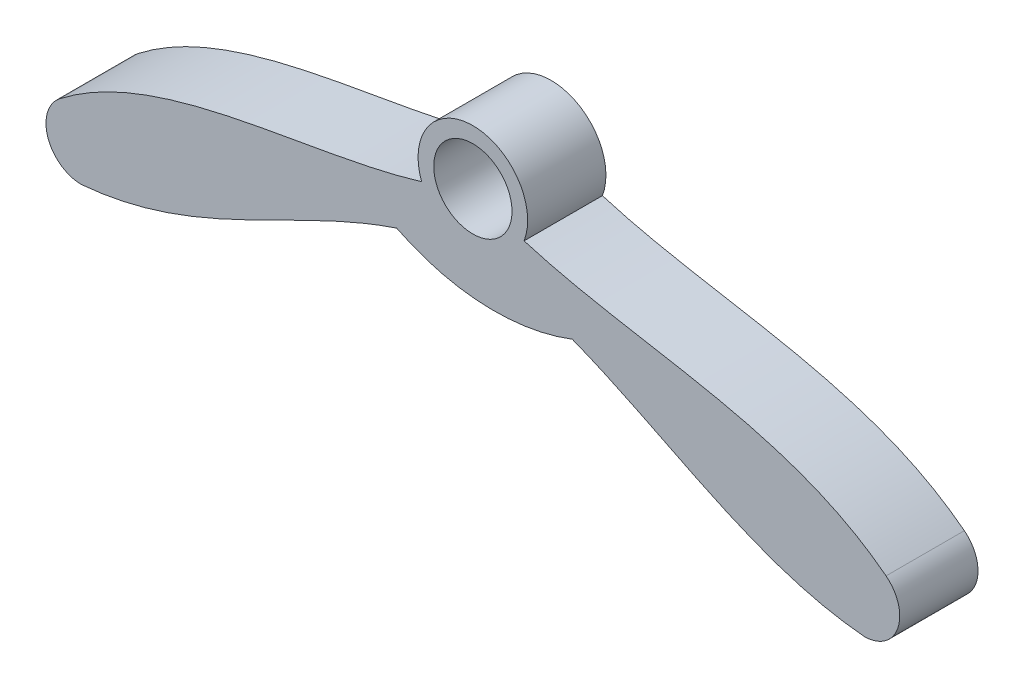
SolidWorks part; units mm, degrees
ref_plane "Front Plane" through (0, 0, 0) normal (0, 0, 1) x (1, 0, 0)
ref_plane "Top Plane" through (0, 0, 0) normal (0, 1, 0) x (1, 0, 0)
ref_plane "Right Plane" through (0, 0, 0) normal (1, 0, 0) x (0, 0, -1)
sketch "Sketch1" plane through (0, 0, 0) normal (0, 0, 1) x (1, 0, 0)
  line L0 (-50, 0) -> (0, 0)
  line L5 (50, 20) -> (-50, 20) construction
  line L6 (50, 20) -> (50, -20) construction
  line L7 (50, -20) -> (-50, -20) construction
  line L8 (-50, 20) -> (-50, -20) construction
  line L9 (50, 20) -> (-50, -20) construction
  line L10 (50, -20) -> (-50, 20) construction
  line L11 (0, -7) -> (0, -6.6081) construction
  circle A4 centre (0, 0) radius 5
  circle A5 centre (0, 0) radius 7
  circle A6 centre (-50, -20) radius 4.5288
  circle A7 centre (50, -20) radius 4.5288
  arc A8 (-9.7361, -9.2135) -> (12.6997, -10.2866) centre (2.6962, 15.6433) ccw
  spline S0 degree 3 poles (0, 0) (-15.4924, -7.3727) (-38.0868, -4.98) (-52.783, -16.4272) knots 0 0 0 0 1 1 1 1
  spline S1 degree 3 poles (-50, -24.5288) (-31.4144, -22.8991) (-18.4569, -9.1065) (0, -7) knots 0 0 0 0 1 1 1 1
  spline S2 degree 3 poles (0, 0) (15.4924, -7.3727) (38.0868, -4.98) (52.783, -16.4272) knots 0 0 0 0 1 1 1 1
  spline S3 degree 3 poles (50, -24.5288) (31.4144, -22.8991) (18.4569, -9.1065) (0, -7) knots 0 0 0 0 1 1 1 1
  dimension "D1" = 10
  dimension "D2" = 2
  dimension "D5" = 50
  dimension "D3" = 100
  dimension "D4" = 20
extrude "Boss-Extrude2" add sketch "Sketch1" along normal blind 10 contours A6 S1 | A6 S1 A5 S0 | S0 A4 L0 A5 | A4 S2 A5 L0 | S2 A4 S0 A5 | A8 S3 S1 | S3 A7 S2 A5 | S3 A7
